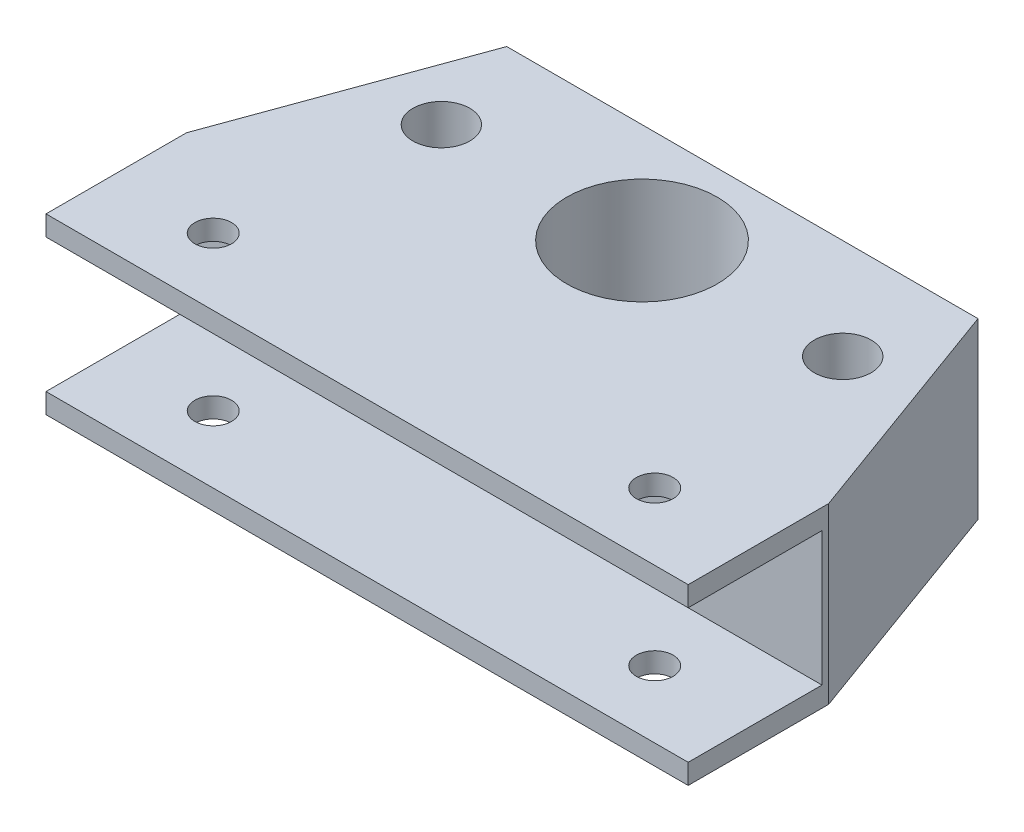
SolidWorks part; units mm, degrees
ref_plane "Спереди" through (0, 0, 0) normal (0, 0, 1) x (1, 0, 0)
ref_plane "Сверху" through (0, 0, 0) normal (0, 1, 0) x (1, 0, 0)
ref_plane "Справа" through (0, 0, 0) normal (1, 0, 0) x (0, 0, -1)
other "Configuration Table"
sketch "Эскиз1" plane through (0, 0, 0) normal (0, 1, 0) x (1, 0, 0)
  line L0 (0, 0) -> (0, 10.5) construction
  line L1 (-48, -10.5) -> (48, -10.5)
  line L2 (-48, -10.5) -> (-48, 10.5)
  line L3 (-48, 10.5) -> (48, 10.5) construction
  line L4 (48, -10.5) -> (48, 10.5)
  line L5 (-48, -10.5) -> (48, 10.5) construction
  line L6 (-48, 10.5) -> (48, -10.5) construction
  line L7 (0, 10.5) -> (0, 64.4132) construction
  line L8 (-48, 10.5) -> (-35.2246, 45.6)
  line L9 (-35.2246, 45.6) -> (0, 45.6)
  line L10 (48, 10.5) -> (35.2246, 45.6)
  line L11 (35.2246, 45.6) -> (0, 45.6)
  circle A0 centre (0, 30.6) radius 11.25
  circle A2 centre (-30, 30.6) radius 11.25 construction
  circle A4 centre (-30, 30.6) radius 4.25
  circle A5 centre (30, 30.6) radius 4.25
  point P0 (0, 0)
  dimension "D3" = 22.5
  dimension "D8" = 15
  dimension "D9" = 8.5
  dimension "D1" = 96
  dimension "D2" = 21
  dimension "D4" = 20.1
  dimension "D7" = 30
  dimension "D5" = 70
  dimension "D6" = 2
extrude "Бобышка-Вытянуть1" add sketch "Эскиз1" along normal mid plane 26
sketch "Эскиз2" plane through (-48, 0, 0) normal (-1, 0, 0) x (0, 0, 1)
  line L0 (0, 0) -> (-10.5, 0) construction
  line L1 (0, 0) -> (10.5, 0) construction
  line L3 (-9.5, 10) -> (10.5, 10)
  line L4 (-10.5, -13) -> (10.5, -13)
  line L5 (10.5, -13) -> (10.5, 13)
  line L6 (10.5, 13) -> (-10.5, 13)
  line L7 (-10.5, 13) -> (-10.5, -13)
  line L8 (-10.5, -13) -> (10.5, -13) construction
  line L9 (10.5, -13) -> (10.5, 13) construction
  line L10 (10.5, 13) -> (-10.5, 13) construction
  line L11 (-10.5, 13) -> (-10.5, -13) construction
  line L12 (-9.5, 10) -> (-9.5, -10)
  line L13 (-9.5, -10) -> (10.5, -10)
  line L14 (10.5, 10) -> (10.5, -10)
  line L15 (-9.5, 10) -> (10.5, -10) construction
  line L16 (-9.5, -10) -> (10.5, 10) construction
  point P6 (0.5, 0)
  point P9 (0.5, 0)
  dimension "D2" = 10
  dimension "D1" = 0
extrude "Вырез-Вытянуть1" cut sketch "Эскиз2" against normal through all
sketch "Sketch1" plane through (0, 10, 0) normal (0, -1, 0) x (1, 0, 0)
  line L0 (33, 10.5) -> (33, -9.5) construction
  line L1 (48, 10.5) -> (-48, 10.5) construction
  line L2 (48, -9.5) -> (-48, -9.5) construction
  line L4 (-33, 10.5) -> (-33, -9.5) construction
  circle A0 centre (-33, 0.5) radius 2.75
  circle A1 centre (33, 0.5) radius 2.75
  dimension "D3" = 5.5
  dimension "D4" = 5.5
  dimension "D1" = 15
  dimension "D2" = 15
extrude "Cut-Extrude1" cut sketch "Sketch1" against normal through all both and the other way through all
equation "\"BearingHole\"= 22.5мм"
